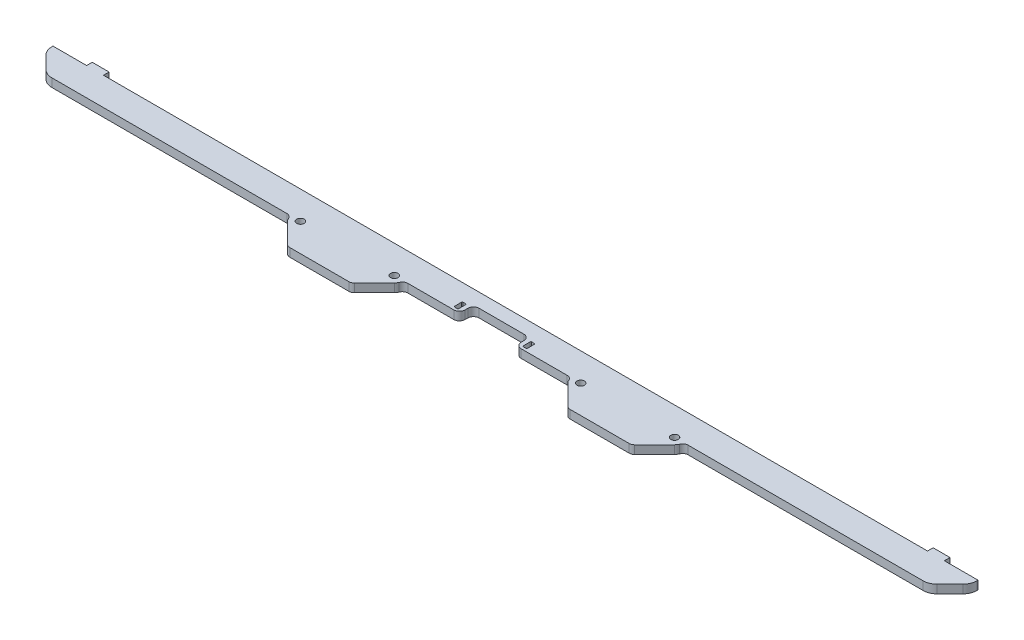
SolidWorks part; units mm, degrees
ref_plane "Front Plane" through (0, 0, 0) normal (0, 0, 1) x (1, 0, 0)
ref_plane "Top Plane" through (0, 0, 0) normal (0, 1, 0) x (1, 0, 0)
ref_plane "Right Plane" through (0, 0, 0) normal (1, 0, 0) x (0, 0, -1)
sketch "Sketch1" plane through (0, 0, 0) normal (0, 1, 0) x (1, 0, 0)
  line L0 (0, 76.0496) -> (0, -79.5915) construction
  line L1 (-165, 5) -> (165, 5)
  line L2 (-165, 5) -> (-165, -5)
  line L3 (-165, -5) -> (165, -5)
  line L4 (165, 5) -> (165, -5)
  line L5 (-165, 5) -> (165, -5) construction
  line L6 (-165, -5) -> (165, 5) construction
  line L7 (153, 5) -> (153, 7)
  line L8 (-153, 5) -> (-147, 5)
  line L9 (-153, 5) -> (-153, 7)
  line L10 (-153, 7) -> (-147, 7)
  line L11 (-147, 5) -> (-147, 7)
  line L12 (153, 5) -> (147, 5)
  line L13 (147, 5) -> (147, 7)
  line L14 (153, 7) -> (147, 7)
  line L15 (-165, 2.5) -> (-157.5, -5)
  line L20 (-150, 7) -> (-150, 5) construction
  line L21 (150, 7) -> (150, 5) construction
  line L22 (165, 2.5) -> (157.5, -5)
  point P0 (0, 0)
  dimension "D1" = 330
  dimension "D2" = 10
  dimension "D3" = 2
  dimension "D4" = 6
  dimension "D5" = 300
  dimension "D6" = 45
  dimension "D7" = 2.5
extrude "Boss-Extrude1" add sketch "Sketch1" along normal blind 3
fillet "Fillet1" radius 5 4 edges at (-157.5, 1.5, 5) (-165, 1.5, -2.5) (157.5, 1.5, 5) (165, 1.5, -2.5)
sketch "Sketch2" plane through (0, 3, 0) normal (0, 1, 0) x (1, 0, 0)
  line L0 (-147, 5) -> (147, 5) construction
  line L1 (70, 5) -> (30, 5)
  line L2 (70, 5) -> (70, -15)
  line L3 (70, -15) -> (30, -15)
  line L4 (30, 5) -> (30, -15)
  line L5 (0, 61.0901) -> (0, -58.498) construction
  line L6 (30, -5) -> (70, -5) construction
  line L7 (50, 5) -> (50, -15) construction
  line L8 (30.9519, -7.2981) -> (38.6538, -15)
  line L9 (69.0481, -7.2981) -> (61.3462, -15)
  line L10 (-70, -15) -> (-30, -15)
  line L11 (-69.0481, -7.2981) -> (-61.3462, -15)
  line L12 (-30.9519, -7.2981) -> (-38.6538, -15)
  circle A0 centre (33.25, -5) radius 1.325
  circle A1 centre (66.75, -5) radius 1.325
  circle A2 centre (33.25, -5) radius 3.25
  circle A3 centre (66.75, -5) radius 3.25
  circle A4 centre (-66.75, -5) radius 1.325
  circle A5 centre (-66.75, -5) radius 3.25
  circle A6 centre (-33.25, -5) radius 1.325
  circle A7 centre (-33.25, -5) radius 3.25
  point P7 (50, -15)
  point P22 (88.5956, -15)
  line M14 (-155.4289, -5) -> (155.4289, -5)
  dimension "D5" = 2.65
  dimension "D1" = 20
  dimension "D2" = 40
  dimension "D3" = 100
  dimension "D4" = 33.5
  dimension "D6" = 45
extrude "Boss-Extrude2" add sketch "Sketch2" against normal up to surface (3 mm away) contours L12 A7 A5 L11 L10 M14 | A5 A4 M14 | A7 A6 M14 | A3 A2 L8 L3 L9 M14 | A2 A0 M14 | A3 A1 M14 up to face at (0, 0, -2.8415)
sketch "Sketch3" plane through (0, 3, 0) normal (0, 1, 0) x (1, 0, 0)
  line L0 (-68.075, -5) -> (-65.425, -5) construction
  line L1 (-34.575, -5) -> (-31.925, -5) construction
  line L2 (0, 5) -> (0, -5) construction
  line L3 (-147, 5) -> (147, 5) construction
  line L4 (-30, -5) -> (30, -5) construction
  line L5 (-10, -2.5) -> (10, -2.5) construction
  line L6 (-10, 0) -> (10, 0)
  line L7 (-10, 0) -> (-10, -5)
  line L8 (-10, -5) -> (10, -5)
  line L9 (10, 0) -> (10, -5)
  line L10 (-10, 0) -> (10, -5) construction
  line L11 (-10, -5) -> (10, 0) construction
  line L12 (13, -1.25) -> (13, -3.75)
  line L13 (-12.75, -1) -> (-11.75, -1)
  line L14 (-13, -1.25) -> (-13, -3.75)
  line L15 (-12.75, -4) -> (-11.75, -4)
  line L16 (-11.5, -1.25) -> (-11.5, -3.75)
  line L17 (12.75, -1) -> (11.75, -1)
  line L18 (11.5, -1.25) -> (11.5, -3.75)
  line L19 (12.75, -4) -> (11.75, -4)
  circle A0 centre (-66.75, -5) radius 1.325
  arc A1 (-68.075, -5) -> (-65.425, -5) centre (-66.75, -5) ccw construction
  circle A2 centre (-33.25, -5) radius 1.325
  arc A3 (-34.575, -5) -> (-31.925, -5) centre (-33.25, -5) ccw construction
  circle A4 centre (33.25, -5) radius 1.325
  arc A5 (31.925, -5) -> (34.575, -5) centre (33.25, -5) ccw construction
  circle A6 centre (66.75, -5) radius 1.325
  arc A7 (65.425, -5) -> (68.075, -5) centre (66.75, -5) ccw construction
  arc A8 (-13, -3.75) -> (-12.75, -4) centre (-12.75, -3.75) ccw
  arc A9 (-11.75, -4) -> (-11.5, -3.75) centre (-11.75, -3.75) ccw
  arc A10 (-11.75, -1) -> (-11.5, -1.25) centre (-11.75, -1.25) cw
  arc A11 (-12.75, -1) -> (-13, -1.25) centre (-12.75, -1.25) ccw
  arc A12 (13, -3.75) -> (12.75, -4) centre (12.75, -3.75) cw
  arc A13 (12.75, -1) -> (13, -1.25) centre (12.75, -1.25) cw
  arc A14 (11.75, -1) -> (11.5, -1.25) centre (11.75, -1.25) ccw
  arc A15 (11.75, -4) -> (11.5, -3.75) centre (11.75, -3.75) cw
  point P32 (0, -2.5)
  point P43 (-13, -2.5)
  point P44 (0, 0)
  point P47 (-13, -4)
  point P52 (-11.5, -1)
  point P55 (-13, -1)
  dimension "D6" = 0.25
  dimension "D1" = 5
  dimension "D2" = 20
  dimension "D3" = 3
  dimension "D4" = 1.5
  dimension "D5" = 1.5
extrude "Cut-Extrude1" cut sketch "Sketch3" against normal up to next
fillet "Fillet2" radius 2 8 edges at (-70, 1.5, 5) (-61.3462, 1.5, 15) (-38.6538, 1.5, 15) (-30, 1.5, 5) (30, 1.5, 5) (70, 1.5, 5) (38.6538, 1.5, 15) (61.3462, 1.5, 15)
fillet "Fillet3" radius 2 4 edges at (10, 1.5, 5) (10, 1.5, 0) (-10, 1.5, 5) (-10, 1.5, 0)
